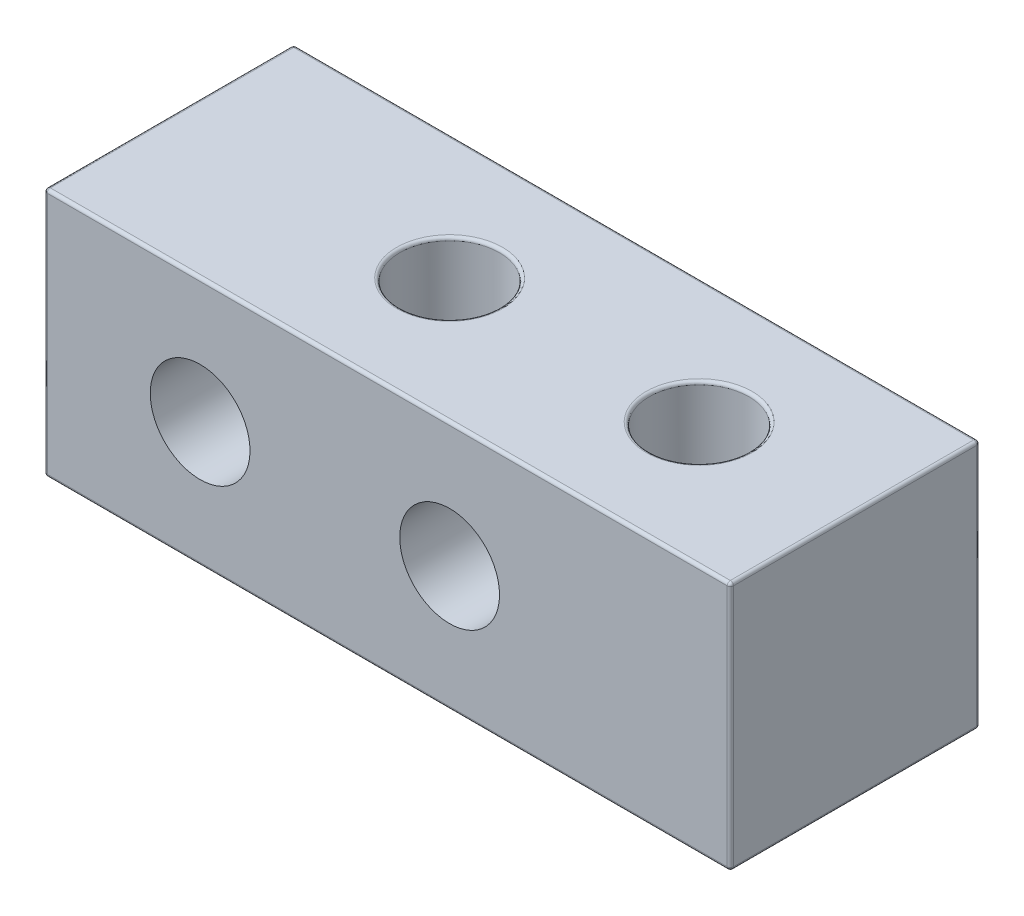
SolidWorks part; units mm, degrees
ref_plane "前视基准面" through (0, 0, 0) normal (0, 0, 1) x (1, 0, 0)
ref_plane "上视基准面" through (0, 0, 0) normal (0, 1, 0) x (1, 0, 0)
ref_plane "右视基准面" through (0, 0, 0) normal (1, 0, 0) x (0, 0, -1)
other "Configuration Table"
sketch "草图1" plane through (0, 0, 0) normal (0, 0, 1) x (1, 0, 0)
  line L1 (0, 0) -> (22, 0)
  line L2 (0, 0) -> (0, -8)
  line L3 (0, -8) -> (22, -8)
  line L4 (22, 0) -> (22, -8)
  dimension "D1" = 22
  dimension "D2" = 8
extrude "凸台-拉伸1" add sketch "草图1" along normal blind 8
sketch "草图2" plane through (0, 0, 8) normal (0, 0, 1) x (1, 0, 0)
  line L0 (0, -4) -> (5, -4) construction
  line L1 (0, 0) -> (0, -8) construction
  line L2 (5, -4) -> (13, -4) construction
  circle A0 centre (5, -4) radius 1.6
  circle A1 centre (13, -4) radius 1.6
  dimension "D1" = 3.2
  dimension "D2" = 3.2
  dimension "D3" = 5
  dimension "D4" = 8
extrude "切除-拉伸1" cut sketch "草图2" against normal through all
sketch "草图3" plane through (0, 0, 0) normal (0, 1, 0) x (1, 0, 0)
  line L0 (22, -4) -> (17, -4) construction
  line L1 (22, -8) -> (22, 0) construction
  line L2 (17, -4) -> (9, -4) construction
  circle A0 centre (17, -4) radius 1.6
  circle A1 centre (9, -4) radius 1.6
  dimension "D3" = 3.2
  dimension "D4" = 3.2
  dimension "D1" = 5
  dimension "D2" = 8
extrude "切除-拉伸2" cut sketch "草图3" against normal through all
fillet "圆角1" radius 0.1 16 edges at (11, -8, 8) (22, -8, 4) (22, -4, 8) (22, 0, 4) (11, 0, 8) (9, 0, 5.6) (17, 0, 5.6) (11, -8, 0) (22, -4, 0) (11, 0, 0) (0, 0, 4) (0, -4, 8) (0, -8, 4) (0, -4, 0) (14.6, -4, 0) (6.6, -4, 0)
